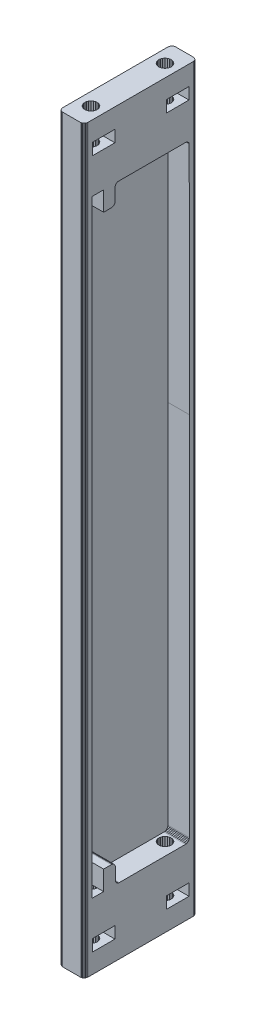
SolidWorks part; units mm, degrees
ref_plane "Front Plane" through (0, 0, 0) normal (0, 0, 1) x (1, 0, 0)
ref_plane "Top Plane" through (0, 0, 0) normal (0, 1, 0) x (1, 0, 0)
ref_plane "Right Plane" through (0, 0, 0) normal (1, 0, 0) x (0, 0, -1)
ref_plane "Plane1" through (0, 130, 0) normal (0, 1, 0) x (1, 0, 0)
sketch "Sketch1" plane through (0, 130, 0) normal (0, 1, 0) x (1, 0, 0)
  line L0 (-2.75, 35.134) -> (-2.5088, 35.0341)
  line L1 (-2.5088, 35.0341) -> (-2.25, 35)
  line L2 (-2.25, 35) -> (2.25, 35)
  line L3 (2.25, 35) -> (2.5088, 35.0341)
  line L4 (2.5088, 35.0341) -> (2.75, 35.134)
  line L5 (2.75, 35.134) -> (2.9571, 35.2929)
  line L6 (2.9571, 35.2929) -> (3.116, 35.5)
  line L7 (3.116, 35.5) -> (3.2159, 35.7412)
  line L8 (3.2159, 35.7412) -> (3.25, 36)
  line L9 (3.25, 36) -> (3.25, 63)
  line L10 (3.25, 63) -> (3.2159, 63.2588)
  line L11 (3.2159, 63.2588) -> (3.116, 63.5)
  line L12 (3.116, 63.5) -> (2.9571, 63.7071)
  line L13 (2.9571, 63.7071) -> (2.75, 63.866)
  line L14 (2.75, 63.866) -> (2.5088, 63.9659)
  line L15 (2.5088, 63.9659) -> (2.25, 64)
  line L16 (2.25, 64) -> (-2.25, 64)
  line L17 (-2.25, 64) -> (-2.5088, 63.9659)
  line L18 (-2.5088, 63.9659) -> (-2.75, 63.866)
  line L19 (-2.75, 63.866) -> (-2.9571, 63.7071)
  line L20 (-2.9571, 63.7071) -> (-3.116, 63.5)
  line L21 (-3.116, 63.5) -> (-3.2159, 63.2588)
  line L22 (-3.2159, 63.2588) -> (-3.25, 63)
  line L23 (-3.25, 63) -> (-3.25, 36)
  line L24 (-3.25, 36) -> (-3.2159, 35.7412)
  line L25 (-3.2159, 35.7412) -> (-3.116, 35.5)
  line L26 (-3.116, 35.5) -> (-2.9571, 35.2929)
  line L27 (-2.9571, 35.2929) -> (-2.75, 35.134)
extrude "Boss-Extrude1" add sketch "Sketch1" against normal blind 190
sketch "Sketch2" plane through (3.25, 0, 0) normal (1, 0, 0) x (0, 0, -1)
  line L0 (37.1, -52) -> (37.1, -55)
  line L1 (37.1, -55) -> (42.9, -55)
  line L2 (42.9, -55) -> (42.9, -52)
  line L3 (42.9, -52) -> (37.1, -52)
  line L4 (36, -60) -> (63, -60) construction
  dimension "D1" = 5
extrude "Cut-Extrude1" cut sketch "Sketch2" against normal through all
sketch "Sketch3" plane through (0, -60, 0) normal (0, -1, 0) x (1, 0, 0)
  line L0 (-1.5455, -40.4141) -> (-1.3856, -40.8)
  line L1 (-1.3856, -40.8) -> (-1.1314, -41.1314)
  line L2 (-1.1314, -41.1314) -> (-0.8, -41.3856)
  line L3 (-0.8, -41.3856) -> (-0.4141, -41.5455)
  line L4 (-0.4141, -41.5455) -> (0, -41.6)
  line L5 (0, -41.6) -> (0.4141, -41.5455)
  line L6 (0.4141, -41.5455) -> (0.8, -41.3856)
  line L7 (0.8, -41.3856) -> (1.1314, -41.1314)
  line L8 (1.1314, -41.1314) -> (1.3856, -40.8)
  line L9 (1.3856, -40.8) -> (1.5455, -40.4141)
  line L10 (1.5455, -40.4141) -> (1.6, -40)
  line L11 (1.6, -40) -> (1.5455, -39.5859)
  line L12 (1.5455, -39.5859) -> (1.3856, -39.2)
  line L13 (1.3856, -39.2) -> (1.1314, -38.8686)
  line L14 (1.1314, -38.8686) -> (0.8, -38.6144)
  line L15 (0.8, -38.6144) -> (0.4141, -38.4545)
  line L16 (0.4141, -38.4545) -> (0, -38.4)
  line L17 (0, -38.4) -> (-0.4141, -38.4545)
  line L18 (-0.4141, -38.4545) -> (-0.8, -38.6144)
  line L19 (-0.8, -38.6144) -> (-1.1314, -38.8686)
  line L20 (-1.1314, -38.8686) -> (-1.3856, -39.2)
  line L21 (-1.3856, -39.2) -> (-1.5455, -39.5859)
  line L22 (-1.5455, -39.5859) -> (-1.6, -40)
  line L23 (-1.6, -40) -> (-1.5455, -40.4141)
extrude "Cut-Extrude2" cut sketch "Sketch3" against normal up to next
sketch "Sketch4" plane through (3.25, 0, 0) normal (1, 0, 0) x (0, 0, -1)
  line L0 (37.1, 125) -> (37.1, 122)
  line L1 (37.1, 122) -> (42.9, 122)
  line L2 (42.9, 122) -> (42.9, 125)
  line L3 (42.9, 125) -> (37.1, 125)
extrude "Cut-Extrude3" cut sketch "Sketch4" against normal through all
sketch "Sketch5" plane through (3.25, 0, 0) normal (1, 0, 0) x (0, 0, -1)
  line L0 (61.9, 125) -> (56.1, 125)
  line L1 (56.1, 125) -> (56.1, 122)
  line L2 (56.1, 122) -> (61.9, 122)
  line L3 (61.9, 122) -> (61.9, 125)
extrude "Cut-Extrude4" cut sketch "Sketch5" against normal through all
sketch "Sketch6" plane through (0, 130, 0) normal (0, 1, 0) x (-1, 0, 0)
  line L0 (1.5455, -39.5859) -> (1.3856, -39.2)
  line L1 (1.3856, -39.2) -> (1.1314, -38.8686)
  line L2 (1.1314, -38.8686) -> (0.8, -38.6144)
  line L3 (0.8, -38.6144) -> (0.4141, -38.4545)
  line L4 (0.4141, -38.4545) -> (0, -38.4)
  line L5 (0, -38.4) -> (-0.4141, -38.4545)
  line L6 (-0.4141, -38.4545) -> (-0.8, -38.6144)
  line L7 (-0.8, -38.6144) -> (-1.1314, -38.8686)
  line L8 (-1.1314, -38.8686) -> (-1.3856, -39.2)
  line L9 (-1.3856, -39.2) -> (-1.5455, -39.5859)
  line L10 (-1.5455, -39.5859) -> (-1.6, -40)
  line L11 (-1.6, -40) -> (-1.5455, -40.4141)
  line L12 (-1.5455, -40.4141) -> (-1.3856, -40.8)
  line L13 (-1.3856, -40.8) -> (-1.1314, -41.1314)
  line L14 (-1.1314, -41.1314) -> (-0.8, -41.3856)
  line L15 (-0.8, -41.3856) -> (-0.4141, -41.5455)
  line L16 (-0.4141, -41.5455) -> (0, -41.6)
  line L17 (0, -41.6) -> (0.4141, -41.5455)
  line L18 (0.4141, -41.5455) -> (0.8, -41.3856)
  line L19 (0.8, -41.3856) -> (1.1314, -41.1314)
  line L20 (1.1314, -41.1314) -> (1.3856, -40.8)
  line L21 (1.3856, -40.8) -> (1.5455, -40.4141)
  line L22 (1.5455, -40.4141) -> (1.6, -40)
  line L23 (1.6, -40) -> (1.5455, -39.5859)
extrude "Cut-Extrude5" cut sketch "Sketch6" against normal up to next
sketch "Sketch7" plane through (0, 130, 0) normal (0, 1, 0) x (-1, 0, 0)
  line L0 (-1.6, -59) -> (-1.5455, -59.4141)
  line L1 (-1.5455, -59.4141) -> (-1.3856, -59.8)
  line L2 (-1.3856, -59.8) -> (-1.1314, -60.1314)
  line L3 (-1.1314, -60.1314) -> (-0.8, -60.3856)
  line L4 (-0.8, -60.3856) -> (-0.4141, -60.5455)
  line L5 (-0.4141, -60.5455) -> (0, -60.6)
  line L6 (0, -60.6) -> (0.4141, -60.5455)
  line L7 (0.4141, -60.5455) -> (0.8, -60.3856)
  line L8 (0.8, -60.3856) -> (1.1314, -60.1314)
  line L9 (1.1314, -60.1314) -> (1.3856, -59.8)
  line L10 (1.3856, -59.8) -> (1.5455, -59.4141)
  line L11 (1.5455, -59.4141) -> (1.6, -59)
  line L12 (1.6, -59) -> (1.5455, -58.5859)
  line L13 (1.5455, -58.5859) -> (1.3856, -58.2)
  line L14 (1.3856, -58.2) -> (1.1314, -57.8686)
  line L15 (1.1314, -57.8686) -> (0.8, -57.6144)
  line L16 (0.8, -57.6144) -> (0.4141, -57.4545)
  line L17 (0.4141, -57.4545) -> (0, -57.4)
  line L18 (0, -57.4) -> (-0.4141, -57.4545)
  line L19 (-0.4141, -57.4545) -> (-0.8, -57.6144)
  line L20 (-0.8, -57.6144) -> (-1.1314, -57.8686)
  line L21 (-1.1314, -57.8686) -> (-1.3856, -58.2)
  line L22 (-1.3856, -58.2) -> (-1.5455, -58.5859)
  line L23 (-1.5455, -58.5859) -> (-1.6, -59)
extrude "Cut-Extrude6" cut sketch "Sketch7" against normal up to next
sketch "Sketch8" plane through (3.25, 0, 0) normal (1, 0, 0) x (0, 0, -1)
  line L0 (56.1, -52) -> (56.1, -55)
  line L1 (56.1, -55) -> (61.9, -55)
  line L2 (61.9, -55) -> (61.9, -52)
  line L3 (61.9, -52) -> (56.1, -52)
  line L4 (36, -60) -> (63, -60) construction
  dimension "D1" = 5
extrude "Cut-Extrude7" cut sketch "Sketch8" against normal through all
sketch "Sketch9" plane through (0, -60, 0) normal (0, -1, 0) x (1, 0, 0)
  line L0 (-0.8, -57.6144) -> (-1.1314, -57.8686)
  line L1 (-1.1314, -57.8686) -> (-1.3856, -58.2)
  line L2 (-1.3856, -58.2) -> (-1.5455, -58.5859)
  line L3 (-1.5455, -58.5859) -> (-1.6, -59)
  line L4 (-1.6, -59) -> (-1.5455, -59.4141)
  line L5 (-1.5455, -59.4141) -> (-1.3856, -59.8)
  line L6 (-1.3856, -59.8) -> (-1.1314, -60.1314)
  line L7 (-1.1314, -60.1314) -> (-0.8, -60.3856)
  line L8 (-0.8, -60.3856) -> (-0.4141, -60.5455)
  line L9 (-0.4141, -60.5455) -> (0, -60.6)
  line L10 (0, -60.6) -> (0.4141, -60.5455)
  line L11 (0.4141, -60.5455) -> (0.8, -60.3856)
  line L12 (0.8, -60.3856) -> (1.1314, -60.1314)
  line L13 (1.1314, -60.1314) -> (1.3856, -59.8)
  line L14 (1.3856, -59.8) -> (1.5455, -59.4141)
  line L15 (1.5455, -59.4141) -> (1.6, -59)
  line L16 (1.6, -59) -> (1.5455, -58.5859)
  line L17 (1.5455, -58.5859) -> (1.3856, -58.2)
  line L18 (1.3856, -58.2) -> (1.1314, -57.8686)
  line L19 (1.1314, -57.8686) -> (0.8, -57.6144)
  line L20 (0.8, -57.6144) -> (0.4141, -57.4545)
  line L21 (0.4141, -57.4545) -> (0, -57.4)
  line L22 (0, -57.4) -> (-0.4141, -57.4545)
  line L23 (-0.4141, -57.4545) -> (-0.8, -57.6144)
extrude "Cut-Extrude8" cut sketch "Sketch9" against normal up to next
sketch "Sketch10" plane through (3.25, 0, 0) normal (1, 0, 0) x (0, 0, -1)
  line L0 (62, -42) -> (62, 52)
  line L1 (62, 52) -> (61.9659, 112.2588)
  line L2 (61.9659, 112.2588) -> (61.866, 112.5)
  line L3 (61.866, 112.5) -> (61.7071, 112.7071)
  line L4 (61.7071, 112.7071) -> (61.5, 112.866)
  line L5 (61.5, 112.866) -> (61.2588, 112.9659)
  line L6 (61.2588, 112.9659) -> (61, 113)
  line L7 (61, 113) -> (44, 113)
  line L8 (42.9659, 108.7412) -> (42.9659, 112.2588)
  line L9 (36, -60) -> (63, -60) construction
  line L16 (42.9659, 108.7412) -> (42.866, 108.5)
  line L17 (42.866, 108.5) -> (42.7071, 108.2929)
  line L18 (42.7071, 108.2929) -> (42.5, 108.134)
  line L19 (42.5, 108.134) -> (42.2588, 108.0341)
  line L20 (42.2588, 108.0341) -> (42, 108)
  line L21 (42, 108) -> (40, 108)
  line L22 (40, 108) -> (40, 113)
  line L23 (40, 113) -> (37, 113)
  line L24 (37, 113) -> (37, -43)
  line L25 (37, -43) -> (40, -43)
  line L26 (40, -43) -> (40, -38)
  line L27 (40, -38) -> (42, -38)
  line L28 (42, -38) -> (42.2588, -38.0341)
  line L29 (42.2588, -38.0341) -> (42.5, -38.134)
  line L30 (42.5, -38.134) -> (42.7071, -38.2929)
  line L31 (42.7071, -38.2929) -> (42.866, -38.5)
  line L32 (42.866, -38.5) -> (42.9659, -38.7412)
  line L33 (42.9659, -38.7412) -> (43, -39)
  line L34 (43, -39) -> (43, -42)
  line L35 (43, -42) -> (43.0341, -42.2588)
  line L36 (43.0341, -42.2588) -> (43.134, -42.5)
  line L37 (43.134, -42.5) -> (43.2929, -42.7071)
  line L38 (43.2929, -42.7071) -> (43.5, -42.866)
  line L39 (43.5, -42.866) -> (43.7412, -42.9659)
  line L40 (43.7412, -42.9659) -> (44, -43)
  line L41 (44, -43) -> (61, -43)
  line L42 (61, -43) -> (61.2588, -42.9659)
  line L43 (61.2588, -42.9659) -> (61.5, -42.866)
  line L44 (61.5, -42.866) -> (61.7071, -42.7071)
  line L45 (61.7071, -42.7071) -> (61.866, -42.5)
  line L46 (61.866, -42.5) -> (61.9659, -42.2588)
  line L47 (61.9659, -42.2588) -> (62, -42)
  line L48 (36, 130) -> (63, 130) construction
  line L49 (62, 35) -> (37, 35) construction
  arc A0 (42.9659, 112.2588) -> (44, 113) centre (43.8536, 112.1124) cw
  dimension "D1" = 156
  dimension "D2" = 17
  dimension "D3" = 5
  dimension "D4" = 5
  dimension "D5" = 78
  dimension "D6" = 17
extrude "Cut-Extrude9" cut sketch "Sketch10" against normal blind 5.5
sketch "Sketch11" plane through (0, 122, 0) normal (0, 1, 0) x (-1, 0, 0)
  line L0 (1.5455, -40.4141) -> (1.6, -40)
  line L1 (1.6, -40) -> (1.5455, -39.5859)
  line L2 (1.5455, -39.5859) -> (1.3856, -39.2)
  line L3 (1.3856, -39.2) -> (1.1314, -38.8686)
  line L4 (1.1314, -38.8686) -> (0.8, -38.6144)
  line L5 (0.8, -38.6144) -> (0.4141, -38.4545)
  line L6 (0.4141, -38.4545) -> (0, -38.4)
  line L7 (0, -38.4) -> (-0.4141, -38.4545)
  line L8 (-0.4141, -38.4545) -> (-0.8, -38.6144)
  line L9 (-0.8, -38.6144) -> (-1.1314, -38.8686)
  line L10 (-1.1314, -38.8686) -> (-1.3856, -39.2)
  line L11 (-1.3856, -39.2) -> (-1.5455, -39.5859)
  line L12 (-1.5455, -39.5859) -> (-1.6, -40)
  line L13 (-1.6, -40) -> (-1.5455, -40.4141)
  line L14 (-1.5455, -40.4141) -> (-1.3856, -40.8)
  line L15 (-1.3856, -40.8) -> (-1.1314, -41.1314)
  line L16 (-1.1314, -41.1314) -> (-0.8, -41.3856)
  line L17 (-0.8, -41.3856) -> (-0.4141, -41.5455)
  line L18 (-0.4141, -41.5455) -> (0, -41.6)
  line L19 (0, -41.6) -> (0.4141, -41.5455)
  line L20 (0.4141, -41.5455) -> (0.8, -41.3856)
  line L21 (0.8, -41.3856) -> (1.1314, -41.1314)
  line L22 (1.1314, -41.1314) -> (1.3856, -40.8)
  line L23 (1.3856, -40.8) -> (1.5455, -40.4141)
extrude "Cut-Extrude10" cut sketch "Sketch11" against normal up to surface (9 mm away) up to face at (0.5, 113, -38.5)
sketch "Sketch12" plane through (0, 122, 0) normal (0, 1, 0) x (-1, 0, 0)
  line L0 (1.5455, -59.4141) -> (1.6, -59)
  line L1 (1.6, -59) -> (1.5455, -58.5859)
  line L2 (1.5455, -58.5859) -> (1.3856, -58.2)
  line L3 (1.3856, -58.2) -> (1.1314, -57.8686)
  line L4 (1.1314, -57.8686) -> (0.8, -57.6144)
  line L5 (0.8, -57.6144) -> (0.4141, -57.4545)
  line L6 (0.4141, -57.4545) -> (0, -57.4)
  line L7 (0, -57.4) -> (-0.4141, -57.4545)
  line L8 (-0.4141, -57.4545) -> (-0.8, -57.6144)
  line L9 (-0.8, -57.6144) -> (-1.1314, -57.8686)
  line L10 (-1.1314, -57.8686) -> (-1.3856, -58.2)
  line L11 (-1.3856, -58.2) -> (-1.5455, -58.5859)
  line L12 (-1.5455, -58.5859) -> (-1.6, -59)
  line L13 (-1.6, -59) -> (-1.5455, -59.4141)
  line L14 (-1.5455, -59.4141) -> (-1.3856, -59.8)
  line L15 (-1.3856, -59.8) -> (-1.1314, -60.1314)
  line L16 (-1.1314, -60.1314) -> (-0.8, -60.3856)
  line L17 (-0.8, -60.3856) -> (-0.4141, -60.5455)
  line L18 (-0.4141, -60.5455) -> (0, -60.6)
  line L19 (0, -60.6) -> (0.4141, -60.5455)
  line L20 (0.4141, -60.5455) -> (0.8, -60.3856)
  line L21 (0.8, -60.3856) -> (1.1314, -60.1314)
  line L22 (1.1314, -60.1314) -> (1.3856, -59.8)
  line L23 (1.3856, -59.8) -> (1.5455, -59.4141)
extrude "Cut-Extrude11" cut sketch "Sketch12" against normal up to surface (9 mm away) up to face at (0.5, 113, -52.5)
sketch "Sketch13" plane through (0, -52, 0) normal (0, -1, 0) x (1, 0, 0)
  line L0 (-0.4141, -41.5455) -> (0, -41.6)
  line L1 (0, -41.6) -> (0.4141, -41.5455)
  line L2 (0.4141, -41.5455) -> (0.8, -41.3856)
  line L3 (0.8, -41.3856) -> (1.1314, -41.1314)
  line L4 (1.1314, -41.1314) -> (1.3856, -40.8)
  line L5 (1.3856, -40.8) -> (1.5455, -40.4141)
  line L6 (1.5455, -40.4141) -> (1.6, -40)
  line L7 (1.6, -40) -> (1.5455, -39.5859)
  line L8 (1.5455, -39.5859) -> (1.3856, -39.2)
  line L9 (1.3856, -39.2) -> (1.1314, -38.8686)
  line L10 (1.1314, -38.8686) -> (0.8, -38.6144)
  line L11 (0.8, -38.6144) -> (0.4141, -38.4545)
  line L12 (0.4141, -38.4545) -> (0, -38.4)
  line L13 (0, -38.4) -> (-0.4141, -38.4545)
  line L14 (-0.4141, -38.4545) -> (-0.8, -38.6144)
  line L15 (-0.8, -38.6144) -> (-1.1314, -38.8686)
  line L16 (-1.1314, -38.8686) -> (-1.3856, -39.2)
  line L17 (-1.3856, -39.2) -> (-1.5455, -39.5859)
  line L18 (-1.5455, -39.5859) -> (-1.6, -40)
  line L19 (-1.6, -40) -> (-1.5455, -40.4141)
  line L20 (-1.5455, -40.4141) -> (-1.3856, -40.8)
  line L21 (-1.3856, -40.8) -> (-1.1314, -41.1314)
  line L22 (-1.1314, -41.1314) -> (-0.8, -41.3856)
  line L23 (-0.8, -41.3856) -> (-0.4141, -41.5455)
extrude "Cut-Extrude12" cut sketch "Sketch13" against normal up to surface (9 mm away) up to face at (0.5, -43, -38.5)
sketch "Sketch14" plane through (0, -52, 0) normal (0, -1, 0) x (1, 0, 0)
  line L0 (-0.4141, -60.5455) -> (0, -60.6)
  line L1 (0, -60.6) -> (0.4141, -60.5455)
  line L2 (0.4141, -60.5455) -> (0.8, -60.3856)
  line L3 (0.8, -60.3856) -> (1.1314, -60.1314)
  line L4 (1.1314, -60.1314) -> (1.3856, -59.8)
  line L5 (1.3856, -59.8) -> (1.5455, -59.4141)
  line L6 (1.5455, -59.4141) -> (1.6, -59)
  line L7 (1.6, -59) -> (1.5455, -58.5859)
  line L8 (1.5455, -58.5859) -> (1.3856, -58.2)
  line L9 (1.3856, -58.2) -> (1.1314, -57.8686)
  line L10 (1.1314, -57.8686) -> (0.8, -57.6144)
  line L11 (0.8, -57.6144) -> (0.4141, -57.4545)
  line L12 (0.4141, -57.4545) -> (0, -57.4)
  line L13 (0, -57.4) -> (-0.4141, -57.4545)
  line L14 (-0.4141, -57.4545) -> (-0.8, -57.6144)
  line L15 (-0.8, -57.6144) -> (-1.1314, -57.8686)
  line L16 (-1.1314, -57.8686) -> (-1.3856, -58.2)
  line L17 (-1.3856, -58.2) -> (-1.5455, -58.5859)
  line L18 (-1.5455, -58.5859) -> (-1.6, -59)
  line L19 (-1.6, -59) -> (-1.5455, -59.4141)
  line L20 (-1.5455, -59.4141) -> (-1.3856, -59.8)
  line L21 (-1.3856, -59.8) -> (-1.1314, -60.1314)
  line L22 (-1.1314, -60.1314) -> (-0.8, -60.3856)
  line L23 (-0.8, -60.3856) -> (-0.4141, -60.5455)
extrude "Cut-Extrude13" cut sketch "Sketch14" against normal up to surface (9 mm away) up to face at (0.5, -43, -52.5)
